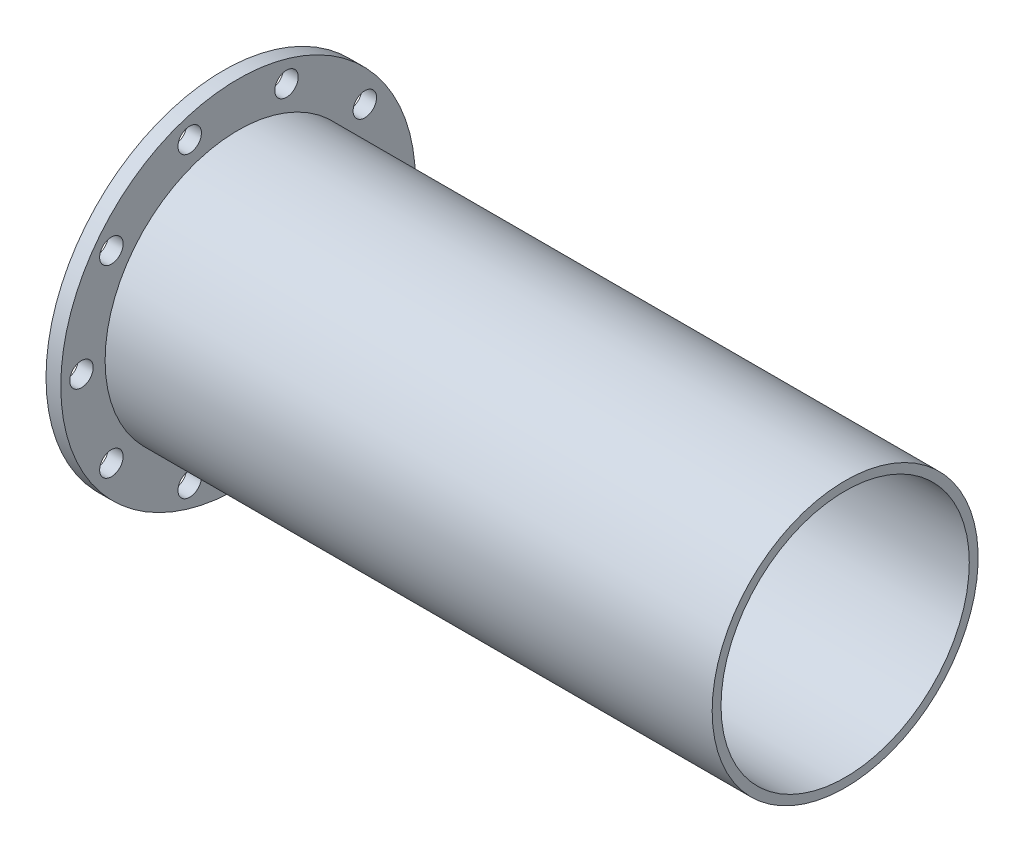
SolidWorks part; units mm, degrees
ref_plane "Front Plane" through (0, 0, 0) normal (0, 0, 1) x (1, 0, 0)
ref_plane "Top Plane" through (0, 0, 0) normal (0, 1, 0) x (1, 0, 0)
ref_plane "Right Plane" through (0, 0, 0) normal (1, 0, 0) x (0, 0, -1)
sketch "Sketch1" plane through (0, 0, 0) normal (0, 0, 1) x (1, 0, 0)
  line L1 (0, 76.2) -> (6.35, 76.2)
  line L2 (6.35, 76.2) -> (6.35, 57.15)
  line L3 (6.35, 57.15) -> (267.208, 57.15)
  line L4 (267.208, 57.15) -> (267.208, 53.34)
  line L5 (267.208, 53.34) -> (0, 53.34)
  line L8 (0, 0) -> (267.208, 0) construction
  line L9 (267.208, 0) -> (267.208, 53.34) construction
  line L10 (0, 76.2) -> (0, 53.34)
  dimension "External Diameter" = 114.3
  dimension "Screwing Space Section" = 6.35
  dimension "Comp" = 152.4
  dimension "Shell Length" = 267.208
  dimension "Wall Thickness" = 3.81
revolve "Revolve1" add sketch "Sketch1" angle 360 about L8
sketch "Sketch2" plane through (6.35, 0, 0) normal (1, 0, 0) x (0, 0, -1)
  point P1 (67.31, 0)
  dimension "D1" = 67.31
hole_wizard "3/8 Clearance Hole1" positions "3DSketch1" profile "Sketch3" hole size "3/8" standard "ANSI Inch" end condition through all
sketch3d "3DSketch1"
  point P12 (6.35, 0, -67.31)
sketch "Sketch3" plane through (6.35, 0, -67.31) normal (0, 1, 0) x (0, 0, -1)
  line L0 (0, 0) -> (0, 6.35)
  line L1 (0, 6.35) -> (5.0419, 6.35)
  line L2 (5.0419, 6.35) -> (5.0419, 0)
  line L5 (5.0419, 0) -> (0, 0)
  line L11 (0, -6.35) -> (0, 107.95) construction
  dimension "Thru Hole Dia." = 10.0838
  dimension "Thru Hole Depth" = 6.35
pattern_circular "CirPattern1" count 10 over 360 about axis through (0, 0, 0) along (1, 0, 0) of "3/8 Clearance Hole1"
